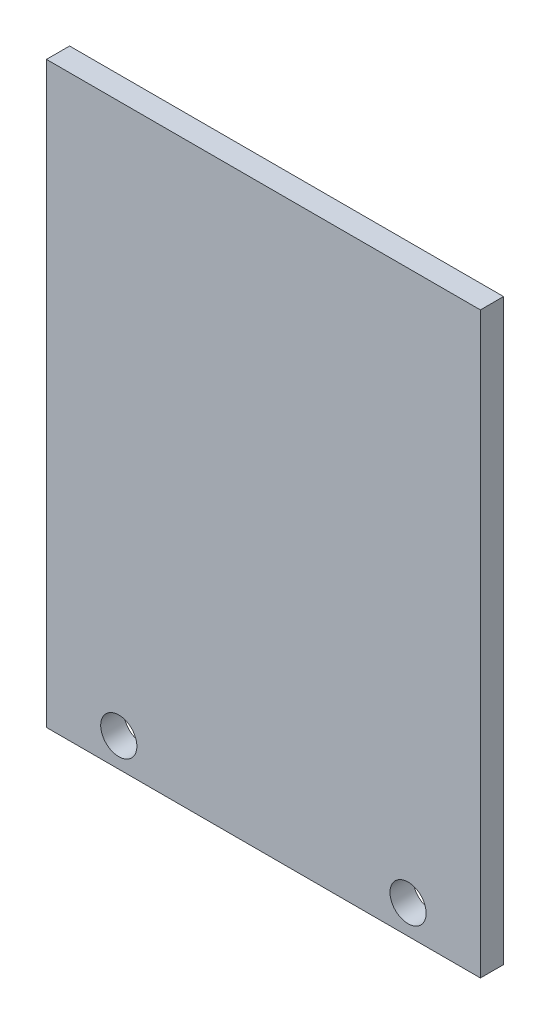
SolidWorks part; units mm, degrees
material "6061-T6 (SS)"
ref_plane "Front Plane" through (0, 0, 0) normal (0, 0, 1) x (1, 0, 0)
ref_plane "Top Plane" through (0, 0, 0) normal (0, 1, 0) x (1, 0, 0)
ref_plane "Right Plane" through (0, 0, 0) normal (1, 0, 0) x (0, 0, -1)
sketch "Sketch1" plane through (0, 0, 0) normal (0, 0, 1) x (1, 0, 0)
  line L1 (-15, -20) -> (15, -20)
  line L2 (-15, -20) -> (-15, 20)
  line L3 (-15, 20) -> (15, 20)
  line L4 (15, -20) -> (15, 20)
  line L5 (-15, -20) -> (15, 20) construction
  line L6 (-15, 20) -> (15, -20) construction
  circle A0 centre (-10, -18) radius 1.25
  circle A1 centre (10, -18) radius 1.25
  point P0 (0, 0)
  point P10 (0, 0)
  dimension "D6" = 2.5
  dimension "D1" = 30
  dimension "D2" = 40
  dimension "D3" = 20
  dimension "D4" = 10
  dimension "D5" = 2
extrude "Boss-Extrude1" add sketch "Sketch1" along normal blind 1.6
equation "\"D4@Sketch1\"=\"D3@Sketch1\"/2"
